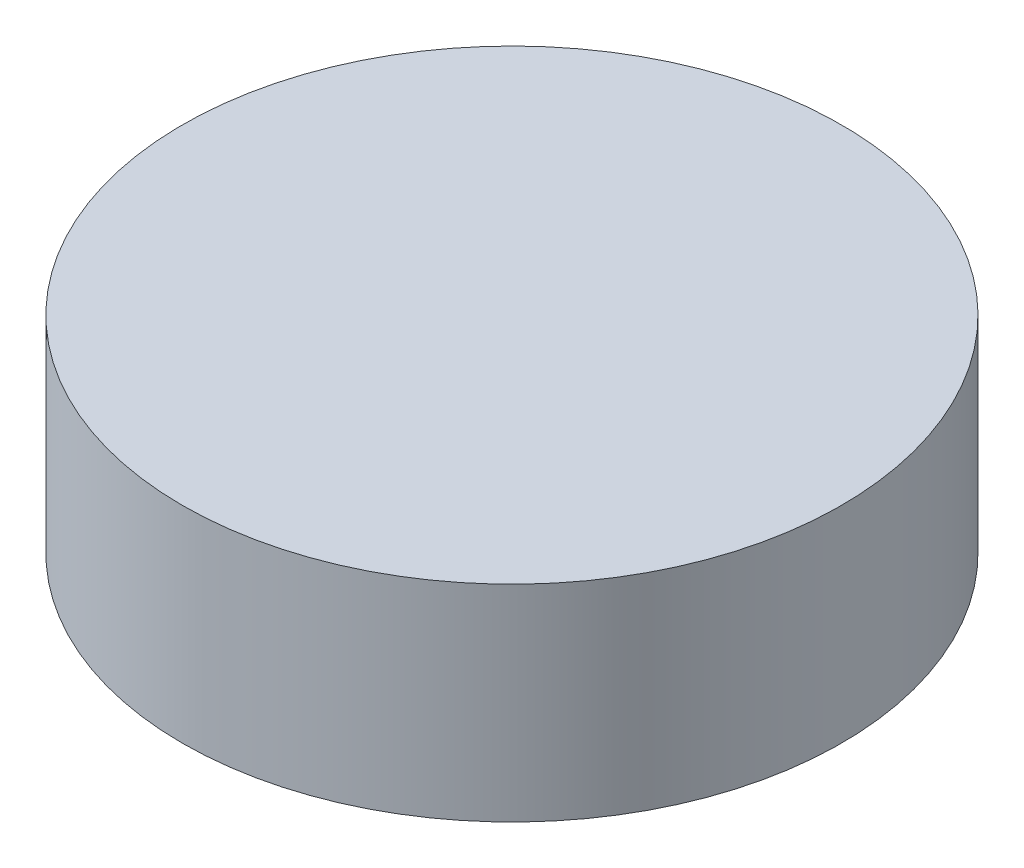
SolidWorks part; units mm, degrees
ref_plane "Front Plane" through (0, 0, 0) normal (0, 0, 1) x (1, 0, 0)
ref_plane "Top Plane" through (0, 0, 0) normal (0, 1, 0) x (1, 0, 0)
ref_plane "Right Plane" through (0, 0, 0) normal (1, 0, 0) x (0, 0, -1)
sketch "Sketch1" plane through (0, 0, 0) normal (0, 1, 0) x (1, 0, 0)
  circle A0 centre (0, 0) radius 2.54
  dimension "D1" = 5.08
extrude "Boss-Extrude1" add sketch "Sketch1" along normal mid plane 1.5875
